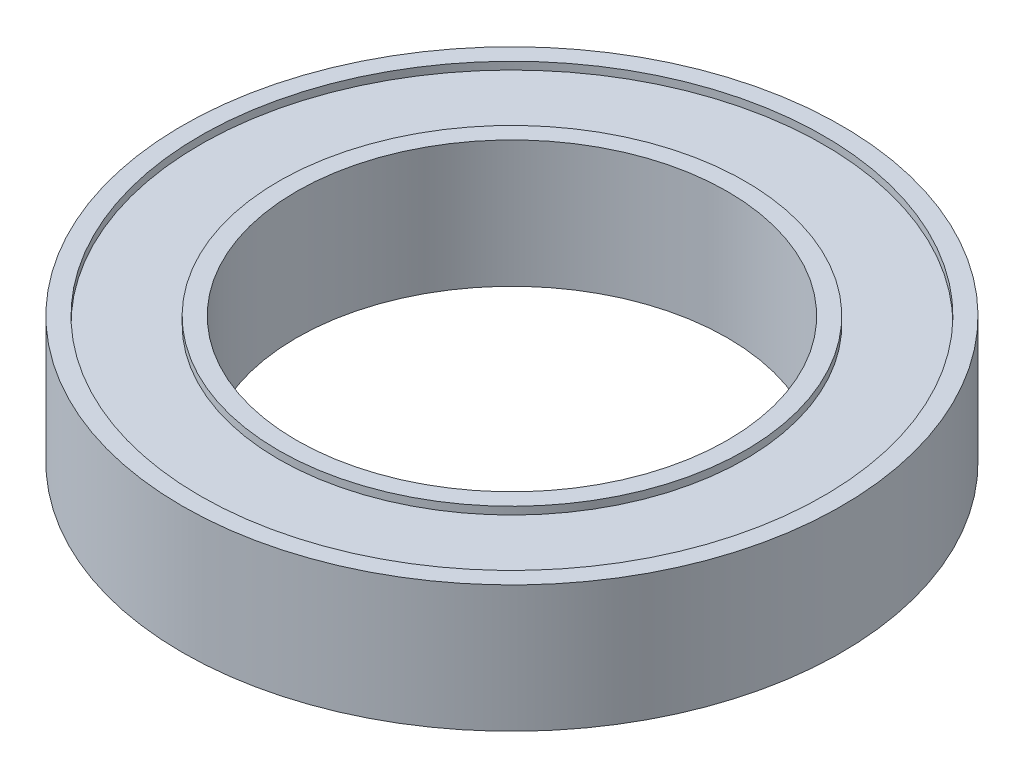
SolidWorks part; units mm, degrees
ref_plane "前视基准面" through (0, 0, 0) normal (0, 0, 1) x (1, 0, 0)
ref_plane "上视基准面" through (0, 0, 0) normal (0, 1, 0) x (1, 0, 0)
ref_plane "右视基准面" through (0, 0, 0) normal (1, 0, 0) x (0, 0, -1)
sketch "草图1" plane through (0, 0, 0) normal (0, 1, 0) x (1, 0, 0)
  circle A0 centre (0, 0) radius 13
  circle A1 centre (0, 0) radius 8.5
  dimension "D1" = 26
  dimension "D2" = 17
extrude "凸台-拉伸1" add sketch "草图1" along normal blind 5
sketch "草图2" plane through (0, 5, 0) normal (0, 1, 0) x (1, 0, 0)
  circle A0 centre (0, 0) radius 12.3
  circle A1 centre (0, 0) radius 9.2
  circle A2 centre (0, 0) radius 13 construction
  circle A3 centre (0, 0) radius 8.5 construction
  dimension "D1" = 0.7
  dimension "D2" = 0.7
extrude "切除-拉伸1" cut sketch "草图2" against normal blind 0.3
ref_plane "基准面4" through (0, 2.5, 0) normal (0, 1, 0) x (1, 0, 0)
mirror "镜向1" about plane through (0, 2.5, 0) normal (0, 1, 0) of "切除-拉伸1"
